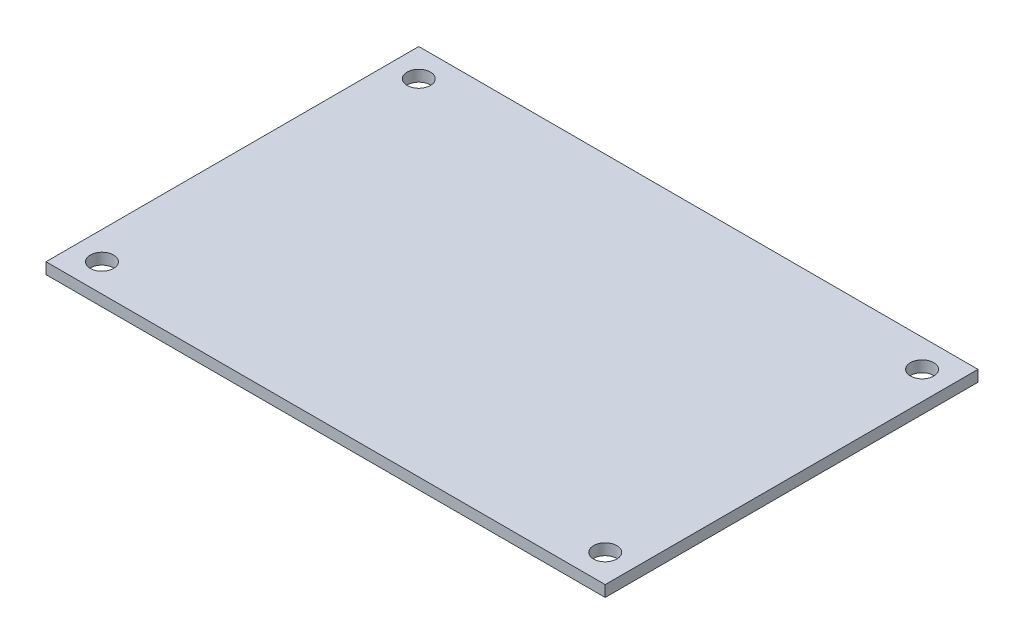
SolidWorks part; units mm, degrees
material "Silicon"
ref_plane "Front Plane" through (0, 0, 0) normal (0, 0, 1) x (1, 0, 0)
ref_plane "Top Plane" through (0, 0, 0) normal (0, 1, 0) x (1, 0, 0)
ref_plane "Right Plane" through (0, 0, 0) normal (1, 0, 0) x (0, 0, -1)
sketch "Sketch1" plane through (0, 0, 0) normal (0, 1, 0) x (1, 0, 0)
  line L0 (-34.29, 21.59) -> (-34.29, -21.59) construction
  line L1 (-38.1, -25.4) -> (38.1, -25.4)
  line L2 (-38.1, -25.4) -> (-38.1, 25.4)
  line L3 (-38.1, 25.4) -> (38.1, 25.4)
  line L4 (38.1, -25.4) -> (38.1, 25.4)
  line L5 (-38.1, -25.4) -> (38.1, 25.4) construction
  line L6 (-38.1, 25.4) -> (38.1, -25.4) construction
  line L7 (-34.29, -21.59) -> (34.29, -21.59) construction
  line L8 (34.29, -21.59) -> (34.29, 21.59) construction
  line L9 (34.29, 21.59) -> (-34.29, 21.59) construction
  line L10 (0, 0) -> (0, 21.59) construction
  line L11 (0, 0) -> (-34.29, 0) construction
  circle A0 centre (34.29, 21.59) radius 1.5875
  circle A1 centre (34.29, -21.59) radius 1.5875
  circle A2 centre (-34.29, -21.59) radius 1.5875
  circle A3 centre (-34.29, 21.59) radius 1.5875
  point P0 (0, 0)
  dimension "D3" = 3.175
  dimension "D1" = 76.2
  dimension "D2" = 50.8
  dimension "D4" = 68.58
  dimension "D5" = 43.18
extrude "Boss-Extrude1" add sketch "Sketch1" along normal blind 1.524
